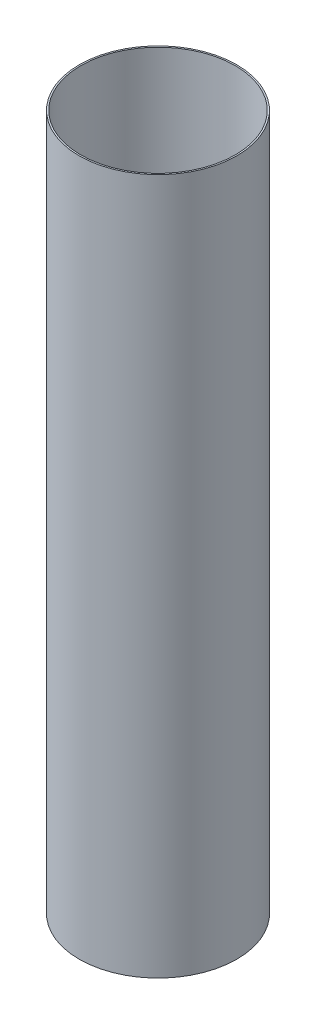
SolidWorks part; units mm, degrees
ref_plane "Спереди" through (0, 0, 0) normal (0, 0, 1) x (1, 0, 0)
ref_plane "Сверху" through (0, 0, 0) normal (0, 1, 0) x (1, 0, 0)
ref_plane "Справа" through (0, 0, 0) normal (1, 0, 0) x (0, 0, -1)
sketch "Эскиз1" plane through (0, 0, 0) normal (0, 1, 0) x (1, 0, 0)
  circle A0 centre (0, 0) radius 51
  circle A1 centre (0, 0) radius 50
  dimension "D1" = 102
  dimension "D2" = 100
extrude "Бобышка-Вытянуть1" add sketch "Эскиз1" along normal blind 450
